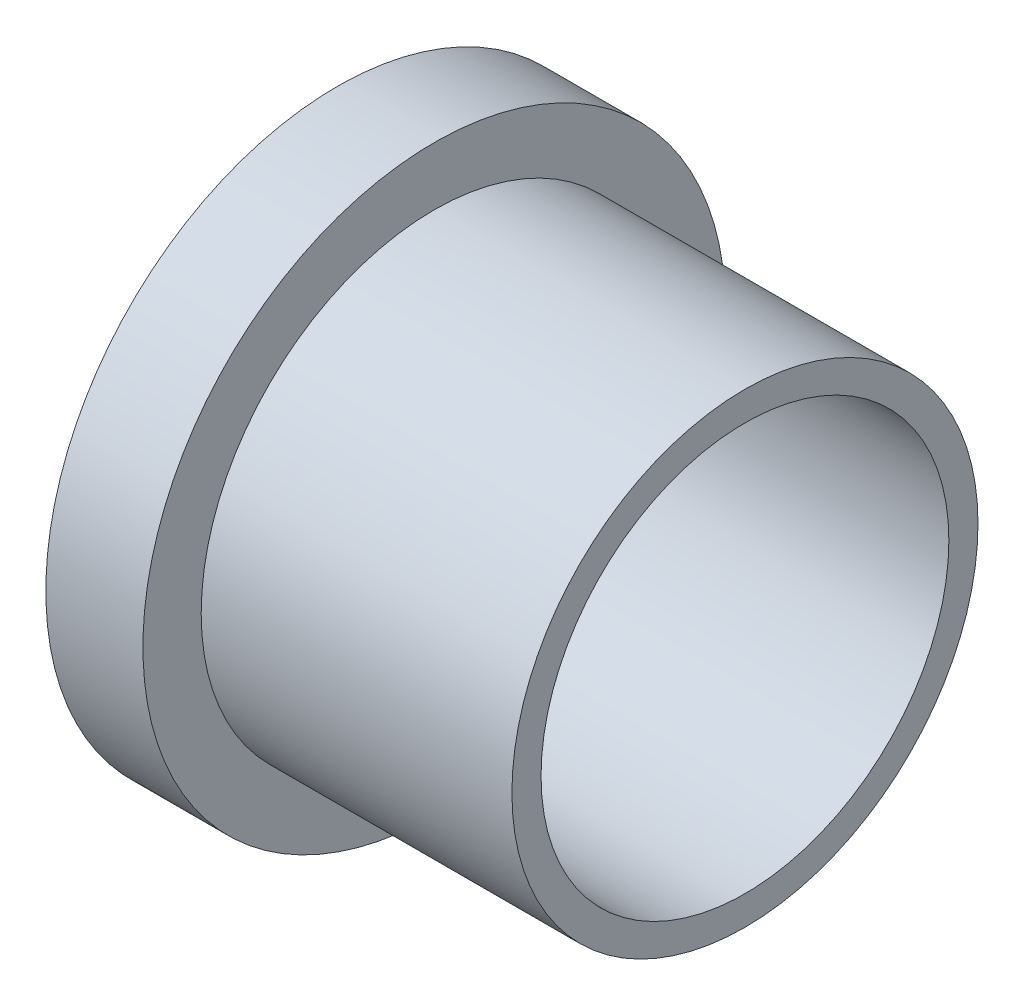
SolidWorks part; units mm, degrees
ref_plane "Front Plane" through (0, 0, 0) normal (0, 0, 1) x (1, 0, 0)
ref_plane "Top Plane" through (0, 0, 0) normal (0, 1, 0) x (1, 0, 0)
ref_plane "Right Plane" through (0, 0, 0) normal (1, 0, 0) x (0, 0, -1)
sketch "Sketch1" plane through (0, 0, 0) normal (1, 0, 0) x (0, 0, -1)
  circle A3 centre (0, 0) radius 15
  dimension "D1" = 30
extrude "Boss-Extrude1" add sketch "Sketch1" along normal mid plane 5 contours A3
sketch "Sketch2" plane through (2.5, 0, 0) normal (1, 0, 0) x (0, 0, -1)
  circle A0 centre (0, 0) radius 12
  circle A1 centre (0, 0) radius 10.5
  dimension "D1" = 24
  dimension "D2" = 21
extrude "Boss-Extrude2" add sketch "Sketch2" along normal blind 16
sketch "Sketch3" plane through (2.5, 0, 0) normal (1, 0, 0) x (0, 0, -1)
  circle A0 centre (0, 0) radius 10.5
extrude "Cut-Extrude1" cut sketch "Sketch3" against normal blind 16
